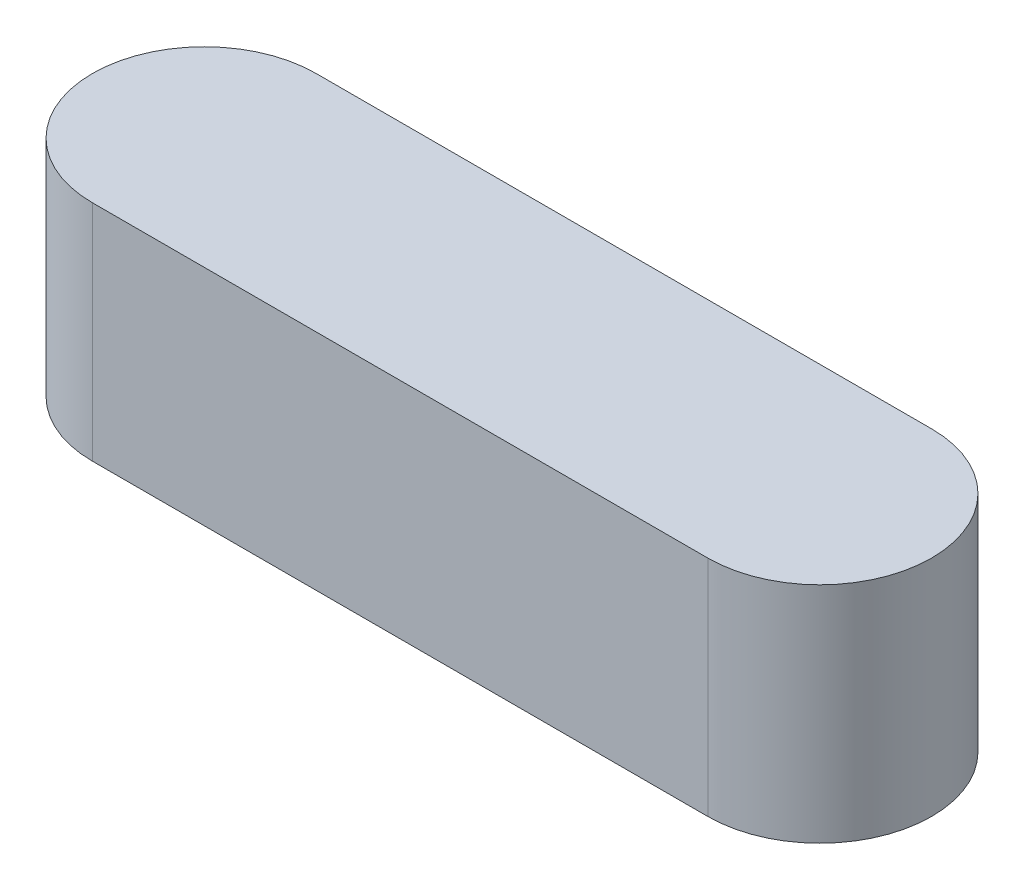
SolidWorks part; units mm, degrees
ref_plane "Front Plane" through (0, 0, 0) normal (0, 0, 1) x (1, 0, 0)
ref_plane "Top Plane" through (0, 0, 0) normal (0, 1, 0) x (1, 0, 0)
ref_plane "Right Plane" through (0, 0, 0) normal (1, 0, 0) x (0, 0, -1)
sketch "Sketch1" plane through (0, 0, 0) normal (0, 1, 0) x (1, 0, 0)
  line L0 (-27.5, 0) -> (27.5, 0) construction
  line L1 (-27.5, 10) -> (27.5, 10)
  line L2 (-27.5, -10) -> (27.5, -10)
  arc A0 (-27.5, 10) -> (-27.5, -10) centre (-27.5, 0) ccw
  arc A1 (27.5, -10) -> (27.5, 10) centre (27.5, 0) ccw
  point P3 (0, 0)
  dimension "D1" = 10
  dimension "D2" = 55
extrude "Boss-Extrude1" add sketch "Sketch1" along normal blind 20
equation "\"D1@Sketch1\" = \"Radius\""
equation "\"D2@Sketch1\" = \"Length\""
equation "\"D1@Boss-Extrude1\" = \"Thickness\""
equation "\"Length\"= 55mm"
equation "\"Radius\"= 10mm"
equation "\"Thickness\"= 20mm"
